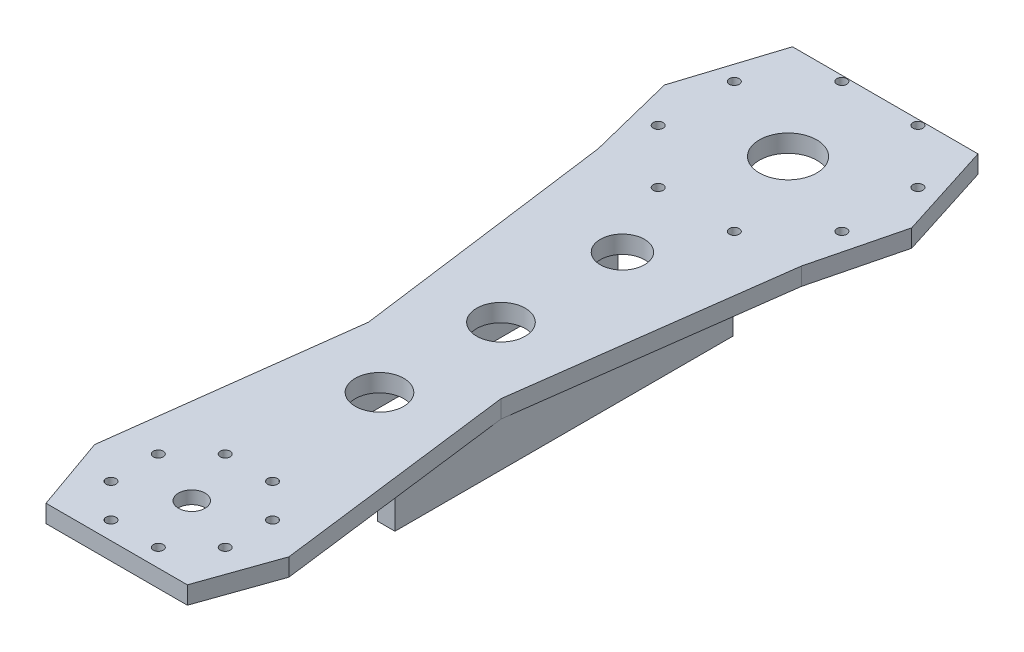
SolidWorks part; units mm, degrees
ref_plane "Front Plane" through (0, 0, 0) normal (0, 0, 1) x (1, 0, 0)
ref_plane "Top Plane" through (0, 0, 0) normal (0, 1, 0) x (1, 0, 0)
ref_plane "Right Plane" through (0, 0, 0) normal (1, 0, 0) x (0, 0, -1)
ref_plane "PL_Thigh_Plate_base" through (0, 30, 0) normal (0, 1, 0) x (1, 0, 0)
sketch "SK_Thigh_Plate" plane through (0, 30, 0) normal (0, 1, 0) x (1, 0, 0)
  line L0 (-32, -34) -> (32, -34)
  line L1 (32, -34) -> (44, 0)
  line L2 (44, 0) -> (30, 110)
  line L3 (30, 110) -> (46, 230)
  line L4 (46, 230) -> (56, 270)
  line L5 (56, 270) -> (42, 314)
  line L6 (42, 314) -> (-42, 314)
  line L7 (-42, 314) -> (-56, 270)
  line L8 (-56, 270) -> (-46, 230)
  line L9 (-46, 230) -> (-30, 110)
  line L10 (-30, 110) -> (-44, 0)
  line L11 (-44, 0) -> (-32, -34)
  circle A0 centre (25.8686, 10.7151) radius 2.25
  circle A1 centre (10.7151, 25.8686) radius 2.25
  circle A2 centre (-10.7151, 25.8686) radius 2.25
  circle A3 centre (-25.8686, 10.7151) radius 2.25
  circle A4 centre (-25.8686, -10.7151) radius 2.25
  circle A5 centre (-10.7151, -25.8686) radius 2.25
  circle A6 centre (10.7151, -25.8686) radius 2.25
  circle A7 centre (25.8686, -10.7151) radius 2.25
  circle A8 centre (41.5746, 287.2208) radius 2.25
  circle A9 centre (17.2208, 311.5746) radius 2.25
  circle A10 centre (-17.2208, 311.5746) radius 2.25
  circle A11 centre (-41.5746, 287.2208) radius 2.25
  circle A12 centre (-41.5746, 252.7792) radius 2.25
  circle A13 centre (-17.2208, 228.4254) radius 2.25
  circle A14 centre (17.2208, 228.4254) radius 2.25
  circle A15 centre (41.5746, 252.7792) radius 2.25
  circle A16 centre (0, 0) radius 6
  circle A17 centre (0, 270) radius 13
  circle A18 centre (0, 85) radius 11
  circle A19 centre (0, 140) radius 11
  circle A20 centre (0, 195) radius 10
  dimension "D23_SK_Thigh_Plate" = 4.5
  dimension "D26_SK_Thigh_Plate" = 4.5
  dimension "D29_SK_Thigh_Plate" = 4.5
  dimension "D32_SK_Thigh_Plate" = 4.5
  dimension "D35_SK_Thigh_Plate" = 4.5
  dimension "D38_SK_Thigh_Plate" = 4.5
  dimension "D41_SK_Thigh_Plate" = 4.5
  dimension "D44_SK_Thigh_Plate" = 4.5
  dimension "D47_SK_Thigh_Plate" = 4.5
  dimension "D50_SK_Thigh_Plate" = 4.5
  dimension "D53_SK_Thigh_Plate" = 4.5
  dimension "D56_SK_Thigh_Plate" = 4.5
  dimension "D59_SK_Thigh_Plate" = 4.5
  dimension "D62_SK_Thigh_Plate" = 4.5
  dimension "D65_SK_Thigh_Plate" = 4.5
  dimension "D68_SK_Thigh_Plate" = 4.5
  dimension "D71_SK_Thigh_Plate" = 12
  dimension "D72_SK_Thigh_Plate" = 26
  dimension "D74_SK_Thigh_Plate" = 22
  dimension "D76_SK_Thigh_Plate" = 22
  dimension "D78_SK_Thigh_Plate" = 20
  dimension "P1" = 32
  dimension "P2" = 34
  dimension "P3" = 32
  dimension "P4" = 34
  dimension "P5" = 44
  dimension "P6" = 30
  dimension "P7" = 110
  dimension "P8" = 46
  dimension "P9" = 230
  dimension "P10" = 56
  dimension "P11" = 270
  dimension "P12" = 42
  dimension "P13" = 314
  dimension "P14" = 42
  dimension "P15" = 314
  dimension "P16" = 56
  dimension "P17" = 270
  dimension "P18" = 46
  dimension "P19" = 230
  dimension "P20" = 30
  dimension "P21" = 110
  dimension "P22" = 44
  dimension "P24" = 25.8686
  dimension "P25" = 10.7151
  dimension "P27" = 10.7151
  dimension "P28" = 25.8686
  dimension "P30" = 10.7151
  dimension "P31" = 25.8686
  dimension "P33" = 25.8686
  dimension "P34" = 10.7151
  dimension "P36" = 25.8686
  dimension "P37" = 10.7151
  dimension "P39" = 10.7151
  dimension "P40" = 25.8686
  dimension "P42" = 10.7151
  dimension "P43" = 25.8686
  dimension "P45" = 25.8686
  dimension "P46" = 10.7151
  dimension "P48" = 41.5746
  dimension "P49" = 287.2208
  dimension "P51" = 17.2208
  dimension "P52" = 311.5746
  dimension "P54" = 17.2208
  dimension "P55" = 311.5746
  dimension "P57" = 41.5746
  dimension "P58" = 287.2208
  dimension "P60" = 41.5746
  dimension "P61" = 252.7792
  dimension "P63" = 17.2208
  dimension "P64" = 228.4254
  dimension "P66" = 17.2208
  dimension "P67" = 228.4254
  dimension "P69" = 41.5746
  dimension "P70" = 252.7792
  dimension "P73" = 270
  dimension "P75" = 85
  dimension "P77" = 140
  dimension "P79" = 195
extrude "Thigh_Plate" add sketch "SK_Thigh_Plate" along normal blind 8
ref_plane "PL_Pitch_Pilot_Recess_base" through (0, 30, 0) normal (0, 1, 0) x (1, 0, 0)
sketch "SK_Pitch_Pilot_Recess" plane through (0, 30, 0) normal (0, 1, 0) x (1, 0, 0)
  circle A0 centre (0, 0) radius 22.15
  dimension "D1_SK_Pitch_Pilot_Recess" = 44.3
extrude "Pitch_Pilot_Recess" cut sketch "SK_Pitch_Pilot_Recess" along normal blind 2.2
ref_plane "PL_Front_Flange_base" through (22, 0, 0) normal (1, 0, 0) x (0, 0, -1)
sketch "SK_Front_Flange" plane through (22, 0, 0) normal (1, 0, 0) x (0, 0, -1)
  line L0 (215, 10) -> (215, 30)
  line L1 (215, 30) -> (62, 30)
  line L2 (62, 30) -> (62, 10)
  line L3 (62, 10) -> (215, 10)
  dimension "P1" = 215
  dimension "P2" = 10
  dimension "P3" = 215
  dimension "P4" = 30
  dimension "P5" = 62
  dimension "P6" = 30
  dimension "P7" = 62
  dimension "P8" = 10
extrude "Front_Flange" add sketch "SK_Front_Flange" along normal blind 8
ref_plane "PL_Back_Flange_base" through (-30, 0, 0) normal (1, 0, 0) x (0, 0, -1)
sketch "SK_Back_Flange" plane through (-30, 0, 0) normal (1, 0, 0) x (0, 0, -1)
  line L0 (215, 10) -> (215, 30)
  line L1 (215, 30) -> (62, 30)
  line L2 (62, 30) -> (62, 10)
  line L3 (62, 10) -> (215, 10)
  dimension "P1" = 215
  dimension "P2" = 10
  dimension "P3" = 215
  dimension "P4" = 30
  dimension "P5" = 62
  dimension "P6" = 30
  dimension "P7" = 62
  dimension "P8" = 10
extrude "Back_Flange" add sketch "SK_Back_Flange" along normal blind 8
equation "\"Thigh_length\" = 270"
equation "\"Thigh_plate_t\" = 8"
